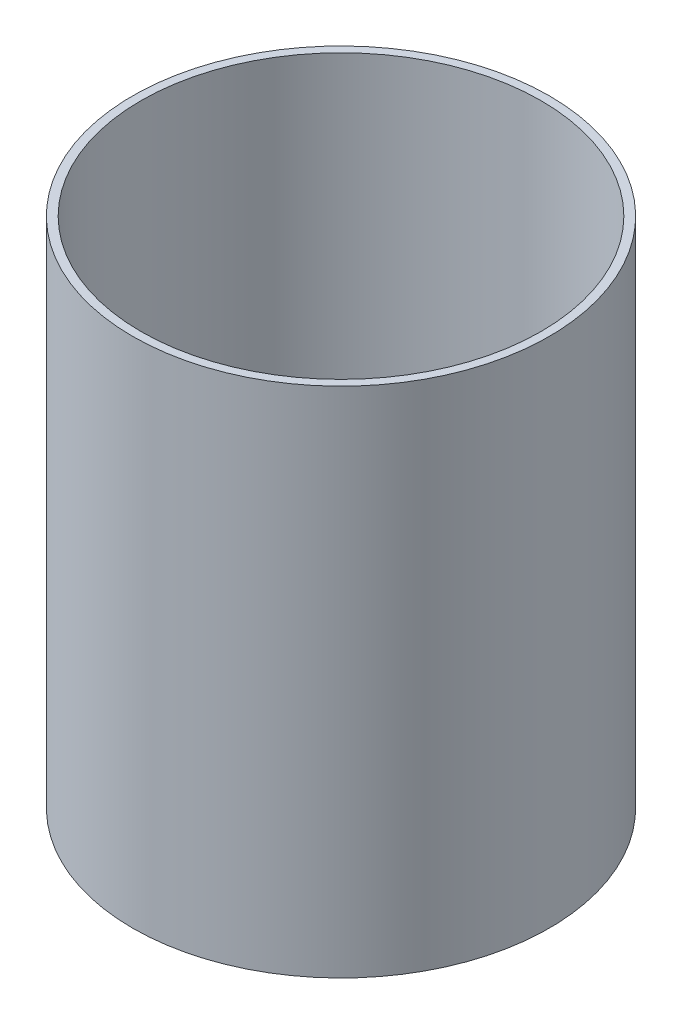
SolidWorks part; units mm, degrees
material "1060 Сплав"
ref_plane "Спереди" through (0, 0, 0) normal (0, 0, 1) x (1, 0, 0)
ref_plane "Сверху" through (0, 0, 0) normal (0, 1, 0) x (1, 0, 0)
ref_plane "Справа" through (0, 0, 0) normal (1, 0, 0) x (0, 0, -1)
sketch "Эскиз1" plane through (0, 0, 0) normal (0, 1, 0) x (1, 0, 0)
  circle A0 centre (0, 0) radius 50
  circle A1 centre (0, 0) radius 48
  dimension "D1" = 100
  dimension "D2" = 96
extrude "Бобышка-Вытянуть1" add sketch "Эскиз1" along normal blind 123
